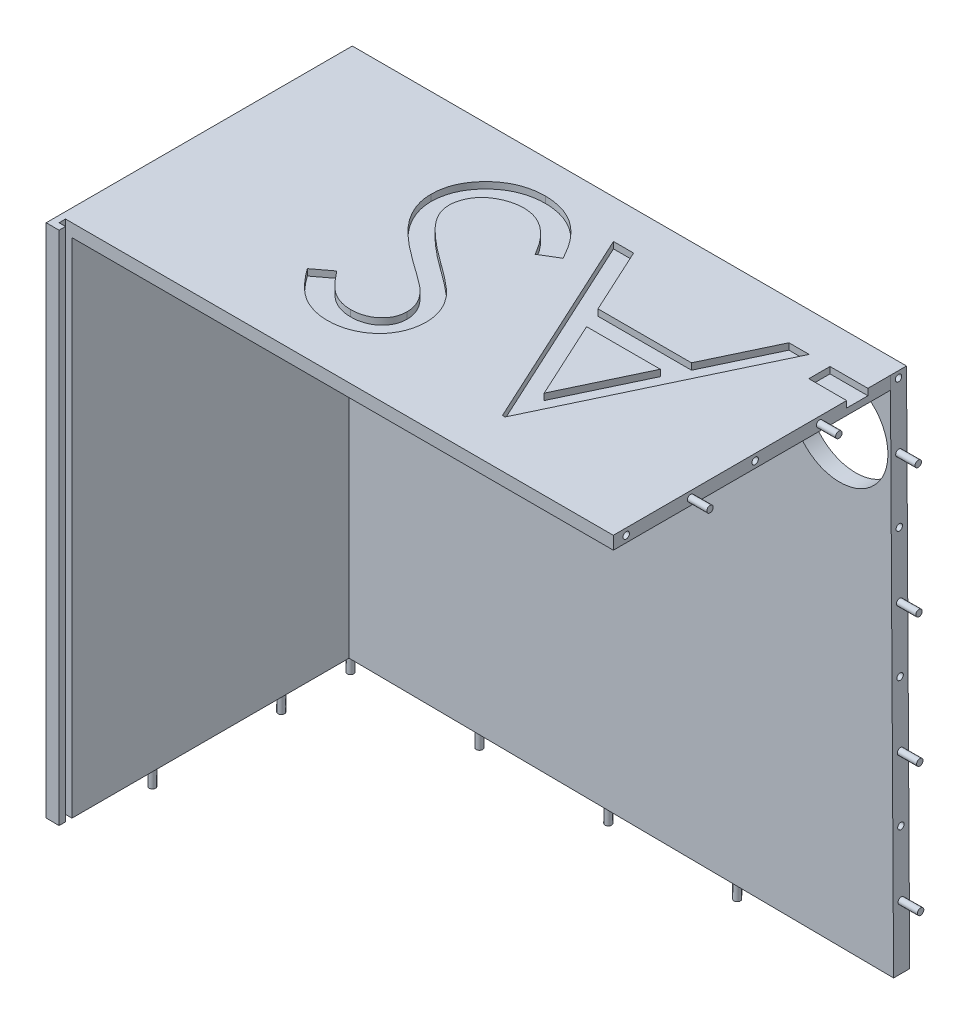
SolidWorks part; units mm, degrees
ref_plane "Alzado" through (0, 0, 0) normal (0, 0, 1) x (1, 0, 0)
ref_plane "Planta" through (0, 0, 0) normal (0, 1, 0) x (1, 0, 0)
ref_plane "Vista lateral" through (0, 0, 0) normal (1, 0, 0) x (0, 0, -1)
sketch "Croquis1" plane through (0, 0, 0) normal (0, 0, 1) x (1, 0, 0)
  line L0 (-86, 80) -> (86, 80) construction
  line L1 (-86, -80) -> (87.9743, -82.988) construction
  line L2 (-86, 80) -> (-86, -80) construction
  line L3 (86, 80) -> (87.9743, -82.988) construction
  line L4 (95.6859, 0) -> (-95.6859, 0) construction
  line L5 (0, -89.6434) -> (0, 89.6434) construction
  line L6 (0, 80) -> (0.9872, -81.494) construction
  line L7 (-86, 0) -> (86.9872, -1.494) construction
  point P1 (0, 80)
  point P3 (-86, 0)
  point P4 (86.9872, -1.494)
  point P5 (0.9872, -81.494)
  dimension "D1" = 174
  dimension "D2" = 172
  dimension "D3" = 160
  dimension "D4" = 163
sketch "Croquis2" plane through (0, 0, 0) normal (0, 0, 1) x (1, 0, 0)
  line L0 (76.1204, 70) -> (2.1204, 70) construction
  line L1 (2.1204, 70) -> (2.1204, -32) construction
  line L2 (2.1204, -32) -> (76.1204, -32) construction
  line L3 (76.1204, -32) -> (76.1204, 70) construction
  line L4 (-86, 80) -> (86, 80) construction
  line L5 (86, 80) -> (87.9743, -82.988) construction
  point P13 (76.1204, 70)
  dimension "D1" = 102
  dimension "D2" = 10
  dimension "D3" = 10
  dimension "D4" = 74
sketch "Croquis3" plane through (0, 0, 0) normal (0, 0, 1) x (1, 0, 0)
  line L0 (-86, 80) -> (86, 80) construction
  line L1 (-86, 80) -> (-86, -80) construction
  line L2 (-81, 70) -> (-19, 70) construction
  line L3 (-19, 70) -> (-19, -25) construction
  line L4 (-19, -25) -> (-81, -25) construction
  line L5 (-81, -25) -> (-81, 70) construction
  line L6 (-19, 58) -> (2.1204, 58) construction
  line L7 (2.1204, 70) -> (2.1204, -32) construction
  line L8 (2.1204, -47) -> (-19, -47) construction
  line L9 (-19, -47) -> (-19, -25) construction
  line L10 (2.1204, -32) -> (2.1204, -47) construction
  point P0 (-81, 70)
  dimension "D1" = 10
  dimension "D2" = 5
  dimension "D3" = 62
  dimension "D4" = 95
  dimension "D5" = 22
  dimension "D6" = 105
sketch "Croquis4" plane through (0, 0, 0) normal (0, 0, 1) x (1, 0, 0)
  line L0 (2.1204, -32) -> (76.1204, -32) construction
  line L1 (22.6942, -40) -> (42.6942, -40) construction
  line L2 (22.6942, -40) -> (22.6942, -41) construction
  line L3 (22.6942, -41) -> (42.6942, -41) construction
  line L4 (72.6942, -41) -> (72.6942, -40) construction
  line L5 (22.6942, -62) -> (42.6942, -62) construction
  line L6 (72.6942, -62) -> (72.6942, -63) construction
  line L7 (72.6942, -63) -> (52.6942, -63) construction
  line L8 (22.6942, -63) -> (22.6942, -62) construction
  line L9 (42.6942, -40) -> (42.6942, -41) construction
  line L11 (52.6942, -63) -> (52.6942, -62) construction
  line L12 (52.6942, -40) -> (72.6942, -40) construction
  line L13 (52.6942, -41) -> (72.6942, -41) construction
  line L14 (42.6942, -62) -> (42.6942, -63) construction
  line L15 (52.6942, -41) -> (52.6942, -40) construction
  line L16 (52.6942, -62) -> (72.6942, -62) construction
  line L17 (42.6942, -63) -> (22.6942, -63) construction
  point P8 (42.6942, -40)
  point P11 (52.6942, -40)
  dimension "D1" = 50
  dimension "D2" = 8
  dimension "D3" = 1
  dimension "D4" = 1
  dimension "D5" = 23
  dimension "D6" = 50
  dimension "D7" = 20
  dimension "D8" = 20
sketch "Croquis6" plane through (0, 0, 0) normal (0, 0, 1) x (1, 0, 0)
  line L0 (-19, -25) -> (-81, -25) construction
  line L1 (-19, -47) -> (-19, -25) construction
  circle A0 centre (-34, -40) radius 12.5 construction
  dimension "D1" = 25
  dimension "D2" = 15
  dimension "D3" = 15
sketch "Croquis7" plane through (0, 0, 0) normal (0, 0, 1) x (1, 0, 0)
  line L0 (2.1204, 70) -> (2.1204, -32) construction
  circle A0 centre (-7.8796, 69.2) radius 7.5 construction
  dimension "D1" = 10
  dimension "D2" = 15
sketch "Croquis8" plane through (0, 0, 0) normal (0, 0, 1) x (1, 0, 0)
  line L0 (-86, -80) -> (87.9743, -82.988) construction
  line L1 (-86, 80) -> (-86, -80) construction
  line L2 (85.9495, -80.953) -> (-84, -78.0341) construction
  line L3 (86, 80) -> (87.9743, -82.988) construction
  line L8 (-84, -78.0341) -> (-84, 78) construction
  line L9 (-84, 78) -> (84.0241, 78) construction
  line L10 (84.0241, 78) -> (85.9495, -80.953) construction
  line L11 (-86, 80) -> (86, 80) construction
  dimension "D1" = 2
  dimension "D2" = 2
  dimension "D3" = 2
  dimension "D4" = 2
sketch "Croquis9" plane through (0, 0, 0) normal (0, 0, 1) x (1, 0, 0)
  line L0 (-71, -25) -> (-71, -78.2573) construction
  line L1 (-86, 80) -> (-86, -80) construction
  line L4 (85.9495, -80.953) -> (-84, -78.0341) construction
  line L5 (-19, -25) -> (-81, -25) construction
  circle A0 centre (-71, -35) radius 0.5 construction
  circle A1 centre (-71, -47) radius 0.5 construction
  circle A2 centre (-71, -55) radius 0.5 construction
  circle A3 centre (-71, -67) radius 0.5 construction
  point P4 (-71, -35)
  point P9 (-71, -47)
  point P10 (-71, -55)
  point P11 (-71, -67)
  dimension "D6" = 1
  dimension "D7" = 1
  dimension "D8" = 1
  dimension "D9" = 1
  dimension "D1" = 15
  dimension "D2" = 10
  dimension "D3" = 12
  dimension "D4" = 8
  dimension "D5" = 12
sketch "Croquis10" plane through (0, 0, 0) normal (0, 0, 1) x (1, 0, 0)
  line L0 (-71, -25) -> (-71, -78.2573) construction
  line L1 (-86, -80) -> (87.9743, -82.988) construction
  line L2 (-53, -43.2562) -> (-71, -43.2562) construction
  line L3 (-53, -70.2562) -> (-71, -70.2562) construction
  line L4 (-71, -70.2562) -> (-71, -69.2562) construction
  line L5 (-71, -69.2562) -> (-53, -69.2562) construction
  line L6 (-53, -69.2562) -> (-53, -70.2562) construction
  line L7 (-71, -43.2562) -> (-71, -44.2562) construction
  line L8 (-71, -44.2562) -> (-53, -44.2562) construction
  line L9 (-53, -44.2562) -> (-53, -43.2562) construction
  line L10 (-86, 80) -> (-86, -80) construction
  point P0 (-71, -70.2562)
  point P1 (-71, -43.2562)
  dimension "D1" = 27
  dimension "D2" = 10
  dimension "D3" = 1
  dimension "D4" = 1
  dimension "D5" = 18
  dimension "D6" = 18
  dimension "D7" = 15
  dimension "D8" = 15
sketch "Croquis11" plane through (0, 0, 0) normal (0, 0, 1) x (1, 0, 0)
  line L0 (-86, -80) -> (87.9743, -82.988) construction
  line L1 (84.0241, 78) -> (85.9495, -80.953) construction
  line L2 (-86, 80) -> (-86, -80) construction
  circle A0 centre (-4.2697, -63.4011) radius 14 construction
  circle A1 centre (-34, -65.8909) radius 10 construction
  dimension "D1" = 18
  dimension "D2" = 28
  dimension "D4" = 20
  dimension "D3" = 90
  dimension "D5" = 15
  dimension "D6" = 52
sketch "Croquis12" plane through (0, 0, 0) normal (0, 0, 1) x (1, 0, 0)
  line L0 (-86, 80) -> (86, 80) construction
  line L1 (-86, 80) -> (-86, -80) construction
  line L3 (86, 80) -> (87.9743, -82.988) construction
  line L4 (-86, -80) -> (87.9743, -82.988) construction
  circle A0 centre (-80, -73.102) radius 2 construction
  circle A1 centre (-80, 74) radius 2 construction
  circle A2 centre (79.0722, 74) radius 2 construction
  circle A3 centre (80.8997, -76.8656) radius 2 construction
  point P0 (-80, 74)
  point P1 (79.0722, 74)
  point P2 (80.8997, -76.8656)
  point P3 (-80, -73.102)
  dimension "D1" = 6
  dimension "D2" = 6
  dimension "D3" = 6
  dimension "D4" = 7
  dimension "D5" = 7
  dimension "D6" = 6
  dimension "D7" = 7
  dimension "D8" = 6
sketch "Croquis13" plane through (0, 0, 0) normal (0, 0, 1) x (1, 0, 0)
  line L0 (76.1204, 70) -> (2.1204, 70) construction
  line L1 (76.1204, -32) -> (76.1204, 70) construction
  line L2 (2.1204, -32) -> (76.1204, -32) construction
  circle A0 centre (72.1204, 63) radius 1.5 construction
  circle A1 centre (72.1204, -26) radius 1.5 construction
  point P0 (72.1204, 63)
  point P7 (72.1204, -26)
  dimension "D3" = 3
  dimension "D6" = 3
  dimension "D1" = 7
  dimension "D2" = 4
  dimension "D4" = 89
  dimension "D5" = 6
sketch "Croquis14" plane through (0, 0, 0) normal (0, 0, 1) x (1, 0, 0)
  line L1 (-19, 70) -> (-19, -25) construction
  line L2 (-19, -25) -> (-81, -25) construction
  circle A0 centre (-49, 45) radius 1.5 construction
  circle A1 centre (-49, -10) radius 1.5 construction
  point P0 (-49, 45)
  point P1 (-49, -10)
  dimension "D3" = 3
  dimension "D4" = 3
  dimension "D1" = 30
  dimension "D2" = 30
  dimension "D5" = 55
  dimension "D6" = 15
sketch "Croquis15" plane through (0, 0, 0) normal (0, 0, 1) x (1, 0, 0)
  line L0 (0, 80) -> (-86, 80)
  line L1 (-86, 80) -> (-86, 0)
  line L2 (-86, 0) -> (0.4936, -0.747)
  line L3 (0, 80) -> (0.9872, -81.494) construction
  line L4 (0.4936, -0.747) -> (0, 80)
extrude "Saliente-Extruir1" add sketch "Croquis15" along normal blind 2.5
sketch "Croquis16" plane through (0, 0, 2.5) normal (0, 0, 1) x (1, 0, 0)
  line L0 (-86, 0) -> (-84, -0.017)
  line L1 (-84, -78.0341) -> (-84, 78) construction
  line L2 (-84, -0.017) -> (-84, 78)
  line L3 (-84, 78) -> (0.012, 78)
  line L4 (-84, 78) -> (84.0241, 78) construction
  line L5 (0.012, 78) -> (0, 80)
  line L6 (0, 80) -> (-86, 80)
  line L7 (-86, 80) -> (-86, 0)
extrude "Saliente-Extruir2" add sketch "Croquis16" along normal blind 45
sketch "Croquis17" plane through (0, 0, 2.5) normal (0, 0, 1) x (1, 0, 0)
  circle A0 centre (-7.8796, 69.2) radius 7.5
  circle A1 centre (-80, 74) radius 2
  circle A2 centre (-49, 45) radius 1.5
extrude "Cortar-Extruir2" cut sketch "Croquis17" against normal blind 45
sketch "Croquis18" plane through (0, 80, 0) normal (0, 1, 0) x (1, 0, 0)
  line L0 (0, -47.5) -> (0, -2.5) construction
  line L1 (0, -46.5) -> (-85, -46.5)
  line L3 (0, -45.5) -> (-85, -45.5)
  line L4 (-85, -46.5) -> (-85, -45.5)
  line L5 (0, -47.5) -> (-86, -47.5) construction
  line L6 (-86, -47.5) -> (-86, 0) construction
  line L7 (0, -45.5) -> (0.8361, -45.5)
  line L8 (0.8361, -45.5) -> (0.8361, -46.5)
  line L9 (0.8361, -46.5) -> (0, -46.5)
  dimension "D1" = 1
  dimension "D2" = 1
  dimension "D3" = 1
extrude "Cortar-Extruir3" cut sketch "Croquis18" against normal blind 105
sketch "Croquis19" plane through (0, 80, 0) normal (0, 1, 0) x (1, 0, 0)
  line L0 (-85, -46.5) -> (0, -46.5) construction
  line L1 (0, -47.5) -> (-84, -47.5)
  line L3 (0, -46.5) -> (-84, -46.5)
  line L4 (-84, -47.5) -> (-84, -46.5)
  line L5 (-86, -47.5) -> (-86, 0) construction
  line L6 (0, -46.5) -> (1.1135, -46.5)
  line L7 (1.1135, -46.5) -> (1.1135, -47.5)
  line L8 (1.1135, -47.5) -> (0, -47.5)
  dimension "D1" = 2
extrude "Cortar-Extruir6" cut sketch "Croquis19" against normal blind 45
sketch "Croquis20" plane through (-86, 0, 0) normal (-1, 0, 0) x (0, 0, 1)
  line L0 (42.8898, 39.728) -> (39.415, 47.8927)
  line L1 (39.415, 47.8927) -> (39.1753, 47.8119)
  line L2 (37.6346, 47.2925) -> (40.7784, 39.5778)
  line L3 (40.7784, 39.5778) -> (37.6346, 31.9301)
  line L4 (37.6346, 31.9301) -> (37.8469, 31.8605)
  line L5 (39.5326, 31.3079) -> (42.8898, 39.728)
  line L6 (36.3789, 46.8518) -> (36.084, 46.7524)
  line L7 (34.4339, 46.1961) -> (37.1108, 39.6272)
  line L8 (37.1108, 39.6272) -> (34.4339, 32.9804)
  line L9 (34.4339, 32.9804) -> (34.7289, 32.8794)
  line L10 (36.4149, 32.3025) -> (39.2927, 39.5778)
  line L11 (39.2927, 39.5778) -> (36.3789, 46.8518)
  line L12 (35.7068, 39.6272) -> (33.1623, 45.796)
  line L13 (33.1623, 45.796) -> (32.9227, 45.7155)
  line L14 (31.3168, 45.1764) -> (33.5779, 39.5778)
  line L15 (33.5779, 39.5778) -> (31.3168, 34.0186)
  line L16 (31.3168, 34.0186) -> (31.6023, 33.9221)
  line L17 (33.1623, 33.3944) -> (35.7068, 39.6272)
  line L18 (32.0938, 39.5734) -> (30.0016, 44.7542)
  line L19 (30.0016, 44.7542) -> (29.751, 44.6646)
  line L20 (28.1105, 44.078) -> (29.9297, 39.5734)
  line L21 (29.9297, 39.5734) -> (28.163, 35.0853)
  line L22 (26.5491, 35.5879) -> (26.8506, 35.486)
  line L23 (30.0016, 34.4635) -> (32.0938, 39.5734)
  line L24 (28.4455, 39.5734) -> (26.7903, 43.6721)
  line L25 (26.7903, 43.6721) -> (26.5491, 43.5912)
  line L26 (24.9537, 43.0556) -> (26.36, 39.5734)
  line L27 (26.36, 39.5734) -> (24.9977, 36.1126)
  line L28 (24.9977, 36.1126) -> (25.2328, 36.0331)
  line L29 (26.8506, 35.486) -> (28.4455, 39.5734)
  line L30 (21.8486, 41.991) -> (22.0971, 42.0745)
  line L31 (23.6913, 42.6096) -> (24.9174, 39.5734)
  line L32 (24.9174, 39.5734) -> (23.6634, 36.5108)
  line L33 (23.6634, 36.5108) -> (23.3836, 36.6097)
  line L34 (21.8114, 37.1651) -> (22.7974, 39.5734)
  line L35 (22.7974, 39.5734) -> (21.8486, 41.991)
  line L36 (21.2829, 39.5734) -> (20.4651, 41.5561)
  line L37 (20.4651, 41.5561) -> (20.219, 41.4735)
  line L38 (18.5972, 40.929) -> (19.1292, 39.5734)
  line L39 (19.1292, 39.5734) -> (18.5703, 38.2084)
  line L40 (18.5703, 38.2084) -> (18.8689, 38.1174)
  line L41 (20.4651, 37.6309) -> (21.2829, 39.5734)
  line L42 (17.6222, 39.5734) -> (17.2913, 40.4164)
  line L43 (17.2913, 40.4164) -> (16.9785, 40.4164)
  line L44 (16.9785, 40.4164) -> (15.4013, 44.2392)
  line L45 (15.4013, 44.2392) -> (5.4718, 44.2392)
  line L46 (5.4718, 44.2392) -> (5.4718, 42.8682)
  line L47 (5.4718, 42.8682) -> (14.4824, 42.8682)
  line L48 (14.4824, 42.8682) -> (15.8823, 39.5734)
  line L49 (15.8823, 39.5734) -> (14.5186, 36.1945)
  line L50 (14.5186, 36.1945) -> (5.4718, 36.1945)
  line L51 (5.4718, 36.1945) -> (5.4718, 34.8825)
  line L52 (5.4718, 34.8825) -> (15.4013, 34.8825)
  line L53 (15.4013, 34.8825) -> (16.9785, 38.695)
  line L54 (16.9785, 38.695) -> (17.2913, 38.695)
  line L55 (17.2913, 38.695) -> (17.6222, 39.5734)
  line L56 (13.7308, 39.5734) -> (13.1549, 40.929)
  line L57 (13.1549, 40.929) -> (5.4718, 40.929)
  line L58 (5.4718, 40.929) -> (5.4718, 38.2084)
  line L59 (5.4718, 38.2084) -> (13.1549, 38.2084)
  line L60 (13.1549, 38.2084) -> (13.7308, 39.5734)
  line L61 (20.219, 41.4735) -> (17.6585, 47.6795)
  line L62 (17.6585, 47.6795) -> (6.4872, 47.6795)
  line L63 (6.4872, 47.6795) -> (6.4157, 47.8927)
  line L64 (6.4157, 47.8927) -> (5.4718, 47.8927)
  line L65 (5.4718, 47.8927) -> (5.4718, 45.9228)
  line L66 (5.4718, 45.9228) -> (5.9437, 45.9228)
  line L67 (5.9437, 45.9228) -> (6.0842, 46.2557)
  line L68 (6.0842, 46.2557) -> (16.7088, 46.2557)
  line L69 (16.7088, 46.2557) -> (18.8689, 41.0202)
  line L70 (18.8689, 38.1174) -> (16.7581, 32.8611)
  line L71 (16.7581, 32.8611) -> (6.1452, 32.8611)
  line L72 (6.1452, 32.8611) -> (5.9999, 33.1338)
  line L73 (5.9999, 33.1338) -> (5.5552, 33.1338)
  line L74 (5.5552, 33.1338) -> (5.5552, 31.222)
  line L75 (5.5552, 31.222) -> (6.5545, 31.222)
  line L76 (6.5545, 31.222) -> (6.5545, 31.4351)
  line L77 (6.5545, 31.4351) -> (17.7279, 31.4351)
  line L78 (17.7279, 31.4351) -> (20.2431, 37.6986)
  line L79 (22.0724, 37.0729) -> (19.3287, 30.2403)
  line L80 (19.3287, 30.2403) -> (19.1519, 29.8001)
  line L81 (26.5491, 43.5912) -> (23.3176, 51.4187)
  line L82 (18.7494, 29.5281) -> (7.2367, 29.5281)
  line L83 (7.2367, 29.5281) -> (7.0897, 29.8001)
  line L84 (7.0897, 29.8001) -> (5.5552, 29.8001)
  line L85 (5.5552, 29.8001) -> (5.5552, 27.8697)
  line L86 (5.5552, 27.8697) -> (8.0192, 27.8697)
  line L87 (8.0192, 27.8697) -> (7.9483, 28.0795)
  line L88 (7.9483, 28.0795) -> (18.7494, 28.0795)
  line L89 (25.2328, 43.1492) -> (24.9537, 43.0556)
  line L90 (20.4651, 29.323) -> (23.3836, 36.6097)
  line L91 (21.8486, 51.3466) -> (25.2328, 43.1492)
  line L92 (23.3836, 42.5063) -> (20.4651, 49.6248)
  line L93 (18.789, 54.4485) -> (9.8741, 54.4485)
  line L94 (9.8741, 54.4485) -> (9.9744, 54.6478)
  line L95 (9.9744, 54.6478) -> (5.6848, 54.6478)
  line L96 (5.6848, 54.6478) -> (5.4668, 52.6261)
  line L97 (5.4668, 52.6261) -> (8.709, 52.6261)
  line L98 (8.709, 52.6261) -> (8.9487, 52.9711)
  line L99 (8.9487, 52.9711) -> (19.3237, 53.0252)
  line L100 (22.0971, 42.0745) -> (19.0616, 49.4265)
  line L101 (26.5491, 35.5879) -> (23.3836, 27.7092)
  line L102 (18.5972, 49.6248) -> (7.1581, 49.6248)
  line L103 (7.1581, 49.6248) -> (6.9631, 49.3065)
  line L104 (6.9631, 49.3065) -> (5.4718, 49.3065)
  line L105 (5.4718, 49.3065) -> (5.4718, 51.2647)
  line L106 (5.4718, 51.2647) -> (7.8979, 51.2647)
  line L107 (7.8979, 51.2647) -> (7.7704, 51.0225)
  line L108 (7.7704, 51.0225) -> (18.5972, 51.0225)
  line L109 (19.1519, 26.1636) -> (9.0884, 26.1636)
  line L110 (22.0724, 28.236) -> (25.2328, 36.0331)
  line L111 (29.751, 44.6646) -> (26.2444, 53.1331)
  line L112 (19.1519, 24.7787) -> (9.9744, 24.7787)
  line L113 (9.9744, 24.7787) -> (10.1399, 24.5235)
  line L114 (10.1399, 24.5235) -> (5.7779, 24.5235)
  line L115 (5.7779, 24.5235) -> (5.6279, 26.4959)
  line L116 (5.6279, 26.4959) -> (8.8947, 26.4959)
  line L117 (9.0884, 26.1636) -> (8.8947, 26.4959)
  line L119 (28.3607, 44.1674) -> (28.1105, 44.078)
  line L120 (24.9537, 52.5987) -> (28.3607, 44.1674)
  line L121 (10.9262, 56.0343) -> (11.0976, 56.3514)
  line L122 (11.0976, 56.3514) -> (19.0462, 56.3514)
  line L123 (23.3836, 42.5063) -> (23.6913, 42.6096)
  line L124 (19.0462, 57.769) -> (12.1006, 57.769)
  line L125 (12.1006, 57.769) -> (12.2501, 58.0454)
  line L126 (12.2501, 58.0454) -> (6.624, 58.0454)
  line L127 (18.8689, 41.0202) -> (18.5972, 40.929)
  line L128 (5.9437, 56.0343) -> (10.9262, 56.0343)
  line L129 (20.2431, 37.6986) -> (20.4651, 37.6309)
  line L130 (29.7375, 34.5528) -> (26.2444, 25.8137)
  line L131 (32.9227, 33.4755) -> (29.3276, 24.7787)
  line L132 (30.0016, 34.4635) -> (29.7375, 34.5528)
  line L133 (28.163, 35.0853) -> (28.3972, 34.9765)
  line L134 (28.3972, 34.9765) -> (24.8306, 26.3788)
  line L135 (18.9064, 22.8261) -> (11.3495, 22.8261)
  line L136 (11.3495, 22.8261) -> (11.0562, 23.1779)
  line L137 (11.0562, 23.1779) -> (6.0393, 23.1779)
  line L138 (19.1519, 19.4632) -> (13.5147, 19.4632)
  line L139 (6.6951, 21.1602) -> (12.3954, 21.1602)
  line L140 (12.3954, 21.1602) -> (12.3067, 21.434)
  line L141 (12.3067, 21.434) -> (19.1519, 21.434)
  line L142 (28.0423, 25.31) -> (31.6023, 33.9221)
  line L143 (32.9227, 33.4755) -> (33.1623, 33.3944)
  line L144 (32.9227, 45.7155) -> (29.0625, 54.95)
  line L145 (28.3461, 53.1656) -> (31.5934, 45.2693)
  line L146 (19.3237, 61.1405) -> (14.2597, 61.1405)
  line L147 (31.5934, 45.2693) -> (31.3168, 45.1764)
  line L148 (14.2597, 61.1405) -> (14.3853, 61.4452)
  line L149 (14.3853, 61.4452) -> (8.4565, 61.4452)
  line L150 (13.5147, 19.4632) -> (13.285, 19.848)
  line L151 (7.1581, 59.3928) -> (13.1549, 59.3928)
  line L152 (13.1549, 59.3928) -> (13.3636, 59.7173)
  line L153 (13.3636, 59.7173) -> (18.5676, 59.7173)
  line L154 (13.285, 19.848) -> (7.4018, 19.848)
  line L155 (36.084, 46.7524) -> (32.6408, 55.1326)
  line L156 (8.6212, 17.8058) -> (14.604, 17.8058)
  line L157 (14.604, 17.8058) -> (14.4239, 18.1075)
  line L158 (14.4239, 18.1075) -> (19.1519, 18.1075)
  line L159 (39.1753, 47.8119) -> (36.084, 55.4933)
  line L160 (31.4757, 54.2285) -> (34.7856, 46.3147)
  line L161 (34.7856, 46.3147) -> (34.4339, 46.1961)
  line L162 (19.6603, 62.9906) -> (15.5117, 62.9906)
  line L163 (15.5117, 62.9906) -> (15.3598, 62.7212)
  line L164 (15.3598, 62.7212) -> (9.5366, 62.7212)
  line L165 (22.0724, 37.0729) -> (21.8114, 37.1651)
  line L166 (11.8275, 64.7788) -> (16.7088, 64.7788)
  line L167 (16.7088, 64.7788) -> (16.5114, 64.4287)
  line L168 (16.5114, 64.4287) -> (19.7545, 64.4287)
  line L169 (34.9925, 54.4568) -> (37.8469, 47.364)
  line L170 (14.2597, 66.1089) -> (17.5331, 66.1089)
  line L171 (17.5331, 66.1089) -> (17.7939, 66.3697)
  line L172 (37.8469, 47.364) -> (37.6346, 47.2925)
  line L173 (36.084, 32.4157) -> (32.6408, 23.9748)
  line L174 (16.8506, 14.503) -> (16.6674, 14.7701)
  line L175 (31.3168, 24.5149) -> (34.7289, 32.8794)
  line L176 (37.8469, 31.8605) -> (34.519, 23.4725)
  line L177 (15.4522, 16.5425) -> (9.7592, 16.5425)
  line L178 (35.7527, 22.9831) -> (39.2729, 31.3931)
  line L179 (39.2729, 31.3931) -> (39.5326, 31.3079)
  line L180 (14.4239, 13.1052) -> (17.7279, 13.1052)
  line L181 (11.9542, 14.4417) -> (16.8506, 14.503)
  line L182 (16.6674, 14.7701) -> (19.5129, 14.7701)
  line L183 (17.7279, 13.1052) -> (17.9479, 12.8852)
  line L184 (15.68, 16.2103) -> (18.3364, 16.2103)
  line L185 (15.68, 16.2103) -> (15.4522, 16.5425)
  line L186 (36.084, 32.4157) -> (36.4149, 32.3025)
  arc A0 (18.7494, 29.5281) -> (19.1519, 29.8001) centre (18.7566, 29.9514) ccw
  arc A1 (21.8486, 51.3466) -> (19.3237, 53.0252) centre (18.4054, 48.9056) ccw
  arc A2 (18.7494, 28.0795) -> (20.4651, 29.323) centre (18.6913, 29.9652) ccw
  arc A3 (23.3176, 51.4187) -> (18.789, 54.4485) centre (18.789, 49.5491) ccw
  arc A4 (20.4651, 49.6248) -> (18.5972, 51.0225) centre (18.729, 49.2516) ccw
  arc A5 (24.9537, 52.5987) -> (19.0462, 56.3514) centre (18.39, 48.7922) ccw
  arc A6 (19.0616, 49.4265) -> (18.5972, 49.6248) centre (18.6651, 49.1407) ccw
  arc A7 (19.1519, 24.7787) -> (23.3836, 27.7092) centre (19.0462, 29.4519) ccw
  arc A8 (19.1519, 26.1636) -> (22.0724, 28.236) centre (18.8318, 29.7089) ccw
  arc A9 (26.2444, 53.1331) -> (19.0462, 57.769) centre (18.6953, 49.3179) ccw
  arc A10 (6.624, 58.0454) -> (5.9437, 56.0343) centre (17.2053, 53.3454) ccw
  arc A11 (6.0393, 23.1779) -> (6.6951, 21.1602) centre (17.3727, 25.746) ccw
  arc A12 (18.9064, 22.8261) -> (24.8306, 26.3788) centre (18.5336, 30.1635) ccw
  arc A13 (8.4565, 61.4452) -> (7.1581, 59.3928) centre (17.8504, 54.0655) ccw
  arc A14 (29.0625, 54.95) -> (19.3237, 61.1405) centre (18.3964, 48.9261) ccw
  arc A15 (19.1519, 21.434) -> (26.2444, 25.8137) centre (18.6912, 30.1128) ccw
  arc A16 (28.3461, 53.1656) -> (18.5676, 59.7173) centre (18.5676, 49.1442) ccw
  arc A17 (7.4018, 19.848) -> (8.6212, 17.8058) centre (13.8426, 22.3086) ccw
  arc A18 (19.1519, 19.4632) -> (28.0423, 25.31) centre (18.5267, 30.0963) ccw
  arc A19 (32.6408, 55.1326) -> (19.7545, 64.4287) centre (18.7176, 49.4118) ccw
  arc A20 (19.1519, 18.1075) -> (29.3276, 24.7787) centre (18.7413, 29.83) ccw
  arc A21 (31.4757, 54.2285) -> (19.6603, 62.9906) centre (18.4312, 48.9859) ccw
  arc A22 (34.9925, 54.4568) -> (17.7939, 66.3697) centre (18.3742, 48.8363) ccw
  arc A23 (11.8275, 64.7788) -> (9.5366, 62.7212) centre (17.8797, 55.7362) ccw
  arc A24 (18.3364, 16.2103) -> (31.3168, 24.5149) centre (18.3364, 30.507) ccw
  arc A25 (17.9479, 12.8852) -> (34.519, 23.4725) centre (18.1314, 30.8601) ccw
  arc A26 (19.5129, 14.7701) -> (32.6408, 23.9748) centre (18.7035, 29.8884) ccw
  arc A27 (9.7592, 16.5425) -> (11.9542, 14.4417) centre (15.1137, 19.9399) ccw
  arc A28 (29.3931, 14.9099) -> (35.7527, 22.9831) centre (20.1314, 28.7473) ccw
  arc A29 (32.0298, 61.9769) -> (14.2597, 66.1089) centre (20.4361, 52.3939) ccw
  arc A30 (14.4239, 13.1052) -> (29.3931, 14.9099) centre (20.5044, 25.6539) ccw
  arc A31 (36.084, 55.4933) -> (32.0298, 61.9769) centre (19.8441, 49.8478) ccw
extrude "Cortar-Extruir8" cut sketch "Croquis20" against normal blind 1
sketch "Croquis21" plane through (0, 80, 0) normal (0, 1, 0) x (1, 0, 0)
  line L0 (0, -6) -> (-70.7381, -6) construction
  line L1 (0, -45.5) -> (0, -2.5) construction
  line L2 (-86, 0) -> (86, 0) construction
  line L4 (0, -9.29) -> (-5.8725, -9.29)
  line L5 (0, -6) -> (0.328, -6)
  line L6 (0, -6) -> (-5.8725, -6)
  line L7 (-5.8725, -9.29) -> (-5.8725, -6)
  line L9 (0, -9.29) -> (0.328, -9.29)
  line L11 (0.328, -6) -> (0.328, -9.29)
  text T0 "AS" font "Century Gothic" height 32
  dimension "D1" = 6
  dimension "D2" = 3.29
extrude "Cortar-Extruir9" cut sketch "Croquis21" against normal blind 1
sketch "Croquis22" plane through (0.489, 0.003, 0) normal (1, 0.0061, 0) x (0, 0, -1)
  line L0 (-1.25, 79.9985) -> (-1.25, -0.75) construction
  line L1 (-2.5, 79.9985) -> (0, 79.9985) construction
  line L2 (-2.5, -0.75) -> (0, -0.75) construction
  circle A0 centre (-1.25, 78.9985) radius 0.5
  circle A2 centre (-1.25, 58.9985) radius 0.5
  circle A3 centre (-1.25, 38.9985) radius 0.5
  circle A4 centre (-1.25, 18.9985) radius 0.5
  dimension "D1" = 1
  dimension "D3" = 20
  dimension "D5" = 20
  dimension "D6" = 20
extrude "Cortar-Extruir10" cut sketch "Croquis22" against normal blind 4
sketch "Croquis24" plane through (0.489, 0.003, 0) normal (1, 0.0061, 0) x (0, 0, -1)
  line L0 (-1.25, 79.9985) -> (-1.25, -0.75) construction
  line L1 (-2.5, 79.9985) -> (0, 79.9985) construction
  line L2 (-2.5, -0.75) -> (0, -0.75) construction
  circle A0 centre (-1.25, 68.9985) radius 0.5
  circle A1 centre (-1.25, 48.9985) radius 0.5
  circle A2 centre (-1.25, 28.9985) radius 0.5
  circle A3 centre (-1.25, 8.9985) radius 0.5
  dimension "D1" = 11
  dimension "D2" = 20
  dimension "D3" = 20
  dimension "D4" = 20
extrude "Saliente-Extruir3" add sketch "Croquis24" along normal blind 3
sketch "Croquis25" plane through (0.4816, 0.0029, 0) normal (1, 0.006, 0) x (0, 0, -1)
  line L0 (-45.5, 78.9985) -> (-34, 78.9985) construction
  line L1 (-45.5, 79.9986) -> (-45.5, 77.9985) construction
  line L3 (-33, 78.9985) -> (-14, 78.9985) construction
  line L4 (-13, 78.9985) -> (-9.29, 78.9985) construction
  circle A0 centre (-43.5, 78.9985) radius 0.5
  circle A2 centre (-23.5, 78.9985) radius 0.5
  dimension "D1" = 2
extrude "Cortar-Extruir11" cut sketch "Croquis25" against normal blind 4
sketch "Croquis27" plane through (0.4816, 0.0029, 0) normal (1, 0.006, 0) x (0, 0, -1)
  line L0 (-45.5, 79.9986) -> (-45.5, 77.9985) construction
  circle A0 centre (-33.5, 78.9985) radius 0.5
  circle A2 centre (-13.5, 78.9985) radius 0.5
  dimension "D1" = 12
  dimension "D2" = 20
extrude "Saliente-Extruir4" add sketch "Croquis27" along normal blind 3
sketch "Croquis28" plane through (-0.0064, -0.7427, 0) normal (-0.0086, -1, 0) x (1, -0.0086, 0)
  line L0 (-85.9968, 1.25) -> (0.5, 1.25) construction
  line L1 (-85.9968, 2.5) -> (-85.9968, 0) construction
  line L2 (0.5, 2.5) -> (0.5, 0) construction
  circle A0 centre (-84.9968, 1.25) radius 0.5
  circle A1 centre (-64.9968, 1.25) radius 0.5
  circle A2 centre (-44.9968, 1.25) radius 0.5
  circle A3 centre (-24.9968, 1.25) radius 0.5
  dimension "D1" = 1
  dimension "D2" = 1
  dimension "D3" = 20
  dimension "D4" = 20
  dimension "D5" = 20
extrude "Saliente-Extruir5" add sketch "Croquis28" along normal blind 3
sketch "Croquis29" plane through (-0.0064, -0.7427, 0) normal (-0.0086, -1, 0) x (1, -0.0086, 0)
  line L0 (-85.9968, 2.5) -> (-85.9968, 0) construction
  circle A0 centre (-74.9968, 1.25) radius 0.5
  circle A1 centre (-54.9968, 1.25) radius 0.5
  circle A2 centre (-34.9968, 1.25) radius 0.5
  circle A3 centre (-14.9968, 1.25) radius 0.5
  dimension "D1" = 11
  dimension "D2" = 20
  dimension "D3" = 20
  dimension "D4" = 20
extrude "Cortar-Extruir12" cut sketch "Croquis29" against normal blind 4
sketch "Croquis30" plane through (-0.0062, -0.7321, 0) normal (-0.0085, -1, 0) x (1, -0.0085, 0)
  line L0 (-84.9968, 47.5) -> (-84.9968, 3.0115) construction
  line L1 (-85.9969, 47.5) -> (-83.9968, 47.5) construction
  line L3 (-85.9969, 0) -> (0.4999, 0) construction
  circle A0 centre (-84.9968, 12) radius 0.5
  circle A1 centre (-84.9968, 32) radius 0.5
  dimension "D1" = 12
  dimension "D2" = 20
extrude "Saliente-Extruir6" add sketch "Croquis30" along normal blind 3
sketch "Croquis31" plane through (-0.0062, -0.7321, 0) normal (-0.0085, -1, 0) x (1, -0.0085, 0)
  line L0 (-85.9969, 0) -> (86.9967, 0) construction
  circle A0 centre (-84.9968, 42) radius 0.5
  circle A1 centre (-84.9968, 22) radius 0.5
  dimension "D1" = 22
  dimension "D2" = 20
extrude "Cortar-Extruir13" cut sketch "Croquis31" against normal blind 4
